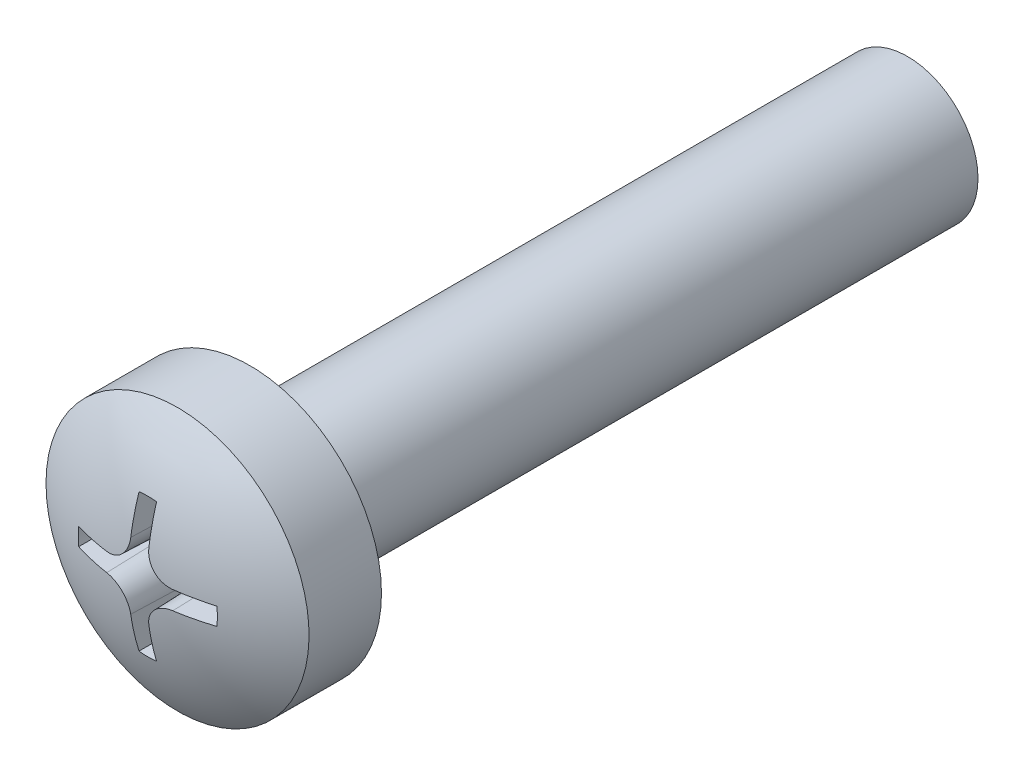
SolidWorks part; units mm, degrees
material "普通碳钢"
ref_plane "Plane1" through (0, 0, 0) normal (0, 0, 1) x (1, 0, 0)
ref_plane "Plane2" through (0, 0, 0) normal (0, 1, 0) x (1, 0, 0)
ref_plane "Plane3" through (0, 0, 0) normal (1, 0, 0) x (0, 0, -1)
sketch "Sketch1" plane through (0, 0, 0) normal (0, 0, 1) x (1, 0, 0)
  circle A0 centre (0, 0) radius 1.5
  dimension "D1" = 3
extrude "Base-Extrude" add sketch "Sketch1" along normal blind 14
sketch "Sketch6" plane through (0, 0, 0) normal (0, 1, 0) x (1, 0, 0)
  line L0 (0, 0.3936) -> (0, -34.4908) construction
  line L1 (0, -14) -> (0, 0) construction
  line L2 (0, -14) -> (2.8, -14)
  line L3 (2.8, -14) -> (2.8, -15.5425)
  line L4 (0, -16.4) -> (0, -14)
  line L5 (-1.5, -14) -> (1.5, -14) construction
  arc A0 (2.8, -15.5425) -> (0, -16.4) centre (0, -11.4) cw
  dimension "D1" = 2.4
  dimension "D9" = 5
  dimension "D8" = 2.8
revolve "Boss-Revolve2" add sketch "Sketch6" angle 360 about L0
ref_plane "Plane6" through (0, 0, 16.7) normal (0, 0, -1) x (-1, 0, 0)
sketch "Sketch7" plane through (0, 0, 16.7) normal (0, 0, -1) x (-1, 0, 0)
  line L0 (-7.1, 0) -> (5.9, 0) construction
  line L1 (0, 7.5) -> (0, -7) construction
  line L2 (0.205, 1.4859) -> (0.205, 0.7082)
  line L3 (0, 0) -> (4.9858, 4.9858) construction
  line L4 (1.4859, 0.205) -> (0.703, 0.2082)
  line L5 (1.4859, -0.205) -> (0.703, -0.2082)
  line L6 (0.205, -1.4859) -> (0.205, -0.7082)
  line L7 (-0.205, -1.4859) -> (-0.205, -0.7082)
  line L8 (-1.4859, -0.205) -> (-0.703, -0.2082)
  line L9 (-1.4859, 0.205) -> (-0.703, 0.2082)
  line L10 (-0.205, 1.4859) -> (-0.205, 0.7082)
  arc A0 (-0.205, 1.4859) -> (0.205, 1.4859) centre (0, 0) cw
  arc A1 (1.4859, -0.205) -> (1.4859, 0.205) centre (0, 0) ccw
  arc A2 (0.205, 0.7082) -> (0.703, 0.2082) centre (0.705, 0.7082) ccw
  arc A3 (-0.205, 0.7082) -> (-0.703, 0.2082) centre (-0.705, 0.7082) cw
  arc A4 (-0.205, -1.4859) -> (0.205, -1.4859) centre (0, 0) ccw
  arc A5 (-0.205, -0.7082) -> (-0.703, -0.2082) centre (-0.705, -0.7082) ccw
  arc A6 (-1.4859, -0.205) -> (-1.4859, 0.205) centre (0, 0) cw
  arc A7 (0.703, -0.2082) -> (0.205, -0.7082) centre (0.705, -0.7082) ccw
  dimension "D1" = 0.5
  dimension "D10" = 1.5
  dimension "D11" = 0.41
extrude "Cut-Extrude1" cut sketch "Sketch7" along normal blind 1.8 draft 2
